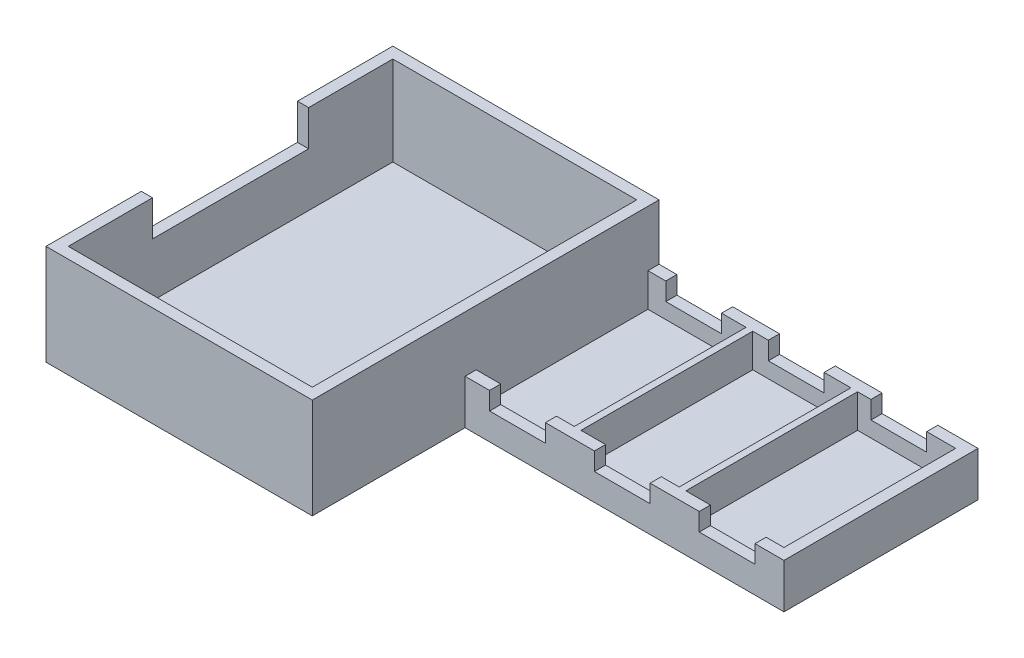
SolidWorks part; units mm, degrees
ref_plane "Frontal Plane" through (0, 0, 0) normal (0, 0, 1) x (1, 0, 0)
ref_plane "Horizontal Plane" through (0, 0, 0) normal (0, 1, 0) x (1, 0, 0)
ref_plane "Profile Plane" through (0, 0, 0) normal (1, 0, 0) x (0, 0, -1)
sketch "Sketch1" plane through (0, 0, 0) normal (0, 1, 0) x (1, 0, 0)
  line L0 (0, 77.75) -> (0, -77.75)
  line L1 (0, 77.75) -> (262.4, 77.75)
  line L2 (0, -77.75) -> (119.4, -77.75)
  line L3 (262.4, 77.75) -> (262.4, -9.25)
  line L4 (262.4, -9.25) -> (119.4, -9.25)
  line L5 (119.4, -9.25) -> (119.4, -77.75)
  line L6 (5, 72.75) -> (257.4, 72.75)
  line L7 (257.4, 72.75) -> (257.4, -4.25)
  line L8 (257.4, -4.25) -> (114.4, -4.25)
  line L9 (114.4, -4.25) -> (114.4, -72.75)
  line L10 (5, -72.75) -> (114.4, -72.75)
  line L11 (5, 72.75) -> (5, -72.75)
  point P4 (0, 0)
  dimension "D1" = 145.5
  dimension "D2" = 109.4
  dimension "D4" = 138
  dimension "D5" = 77
  dimension "D3" = 5
extrude "Boss-Extrude1" add sketch "Sketch1" along normal blind 40
sketch "Sketch3" plane through (0, 0, 0) normal (0, -1, 0) x (1, 0, 0)
  line L0 (119.4, 77.75) -> (119.4, 9.25)
  line L1 (119.4, 77.75) -> (119.4, 9.25)
  line L2 (119.4, 9.25) -> (262.4, 9.25)
  line L3 (119.4, 9.25) -> (262.4, 9.25)
  line L4 (262.4, 9.25) -> (262.4, -77.75)
  line L5 (262.4, 9.25) -> (262.4, -77.75)
  line L6 (262.4, -77.75) -> (0, -77.75)
  line L7 (262.4, -77.75) -> (0, -77.75)
  line L8 (0, -77.75) -> (0, 77.75)
  line L9 (0, -77.75) -> (0, 77.75)
  line L10 (0, 77.75) -> (119.4, 77.75)
  line L11 (0, 77.75) -> (119.4, 77.75)
extrude "Boss-Extrude2" add sketch "Sketch3" along normal blind 5
sketch "Sketch4" plane through (0, 0, 0) normal (0, 1, 0) x (1, 0, 0)
  line L0 (114.4, -4.25) -> (114.4, 72.75)
  line L1 (257.4, 72.75) -> (5, 72.75) construction
  line L2 (114.4, -4.25) -> (119.4, -4.25)
  line L3 (114.4, -4.25) -> (257.4, -4.25) construction
  line L4 (119.4, -4.25) -> (119.4, 72.75)
  line L5 (119.4, 72.75) -> (114.4, 72.75)
  line L7 (163.4, 72.75) -> (163.4, -4.25)
  line L8 (114.4, -4.25) -> (257.4, -4.25) construction
  line L9 (163.4, -4.25) -> (166.4, -4.25)
  line L10 (166.4, -4.25) -> (166.4, 72.75)
  line L11 (257.4, 72.75) -> (5, 72.75) construction
  line L12 (166.4, 72.75) -> (163.4, 72.75)
  line L13 (210.4, 72.75) -> (210.4, -4.25)
  line L14 (210.4, -4.25) -> (213.4, -4.25)
  line L15 (213.4, -4.25) -> (213.4, 72.75)
  line L16 (213.4, 72.75) -> (210.4, 72.75)
  point P20 (145.9914, 71.75)
  dimension "D1" = 3
  dimension "D2" = 44
  dimension "D3" = 44
extrude "Boss-Extrude3" add sketch "Sketch4" along normal up to surface (40 mm away) up to face at (127.2667, 40, 3.0833)
sketch "Sketch5" plane through (0, 40, 0) normal (0, 1, 0) x (1, 0, 0)
  line L0 (119.4, 77.75) -> (119.4, -9.25)
  line L1 (262.4, 77.75) -> (0, 77.75) construction
  line L2 (119.4, -9.25) -> (262.4, -9.25)
  line L3 (262.4, -9.25) -> (262.4, 77.75)
  line L4 (262.4, 77.75) -> (119.4, 77.75)
extrude "Cut-Extrude1" cut sketch "Sketch5" against normal offset from surface (25 mm away) 15 up to face at (141.4, 0, -34.25)
sketch "Sketch6" plane through (0, 15, 0) normal (0, 1, 0) x (1, 0, 0)
  line L0 (130.4, -4.25) -> (130.4, -9.25)
  line L1 (119.4, -4.25) -> (163.4, -4.25) construction
  line L2 (262.4, -9.25) -> (119.4, -9.25) construction
  line L3 (130.4, -9.25) -> (155.4, -9.25)
  line L4 (155.4, -9.25) -> (155.4, -4.25)
  line L5 (119.4, -4.25) -> (163.4, -4.25) construction
  line L6 (155.4, -4.25) -> (130.4, -4.25)
  line L7 (163.4, 72.75) -> (119.4, 72.75) construction
  line L8 (202.4, -4.25) -> (177.4, -4.25)
  line L9 (177.4, -4.25) -> (177.4, -9.25)
  line L10 (177.4, -9.25) -> (202.4, -9.25)
  line L11 (202.4, -9.25) -> (202.4, -4.25)
  line L12 (249.4, -4.25) -> (224.4, -4.25)
  line L13 (224.4, -4.25) -> (224.4, -9.25)
  line L14 (224.4, -9.25) -> (249.4, -9.25)
  line L15 (249.4, -9.25) -> (249.4, -4.25)
  line L16 (155.4, -4.25) -> (202.4, -4.25) construction
  line L17 (127.4, 77.75) -> (127.4, 72.75)
  line L18 (119.4, 77.75) -> (262.4, 77.75) construction
  line L19 (127.4, 72.75) -> (152.4, 72.75)
  line L20 (152.4, 72.75) -> (152.4, 77.75)
  line L21 (152.4, 77.75) -> (127.4, 77.75)
  line L22 (198.4, 77.75) -> (173.4, 77.75)
  line L23 (173.4, 77.75) -> (173.4, 72.75)
  line L24 (173.4, 72.75) -> (198.4, 72.75)
  line L25 (198.4, 72.75) -> (198.4, 77.75)
  line L26 (244.4, 77.75) -> (219.4, 77.75)
  line L27 (219.4, 77.75) -> (219.4, 72.75)
  line L28 (219.4, 72.75) -> (244.4, 72.75)
  line L29 (244.4, 72.75) -> (244.4, 77.75)
  line L30 (152.4, 77.75) -> (198.4, 77.75) construction
  point P12 (141.4, 72.75)
  point P13 (141.4, -4.25)
  point P31 (142.9, -9.25)
  point P32 (139.9, 72.75)
  dimension "D1" = 25
  dimension "D3" = 47
  dimension "D4" = 1.5
  dimension "D5" = 25
  dimension "D7" = 46
  dimension "D8" = 1.5
  dimension "D2" = 3
  dimension "D6" = 3
extrude "Cut-Extrude2" cut sketch "Sketch6" against normal offset from surface (8 mm away) 7 up to face at (141.4, 0, -34.25)
sketch "Sketch7" plane through (0, 40, 0) normal (0, 1, 0) x (1, 0, 0)
  line L0 (0, 35) -> (0, -35)
  line L1 (0, 77.75) -> (0, -77.75) construction
  line L2 (0, -35) -> (5, -35)
  line L3 (5, 72.75) -> (5, -72.75) construction
  line L4 (5, -35) -> (5, 35)
  line L5 (5, 35) -> (0, 35)
  point P5 (0, 0)
  dimension "D1" = 70
extrude "Cut-Extrude3" cut sketch "Sketch7" against normal offset from surface (16 mm away) 24 up to face at (59.7, 0, 0)
sketch "Sketch8" [suppressed] plane through (0, 0, 0) normal (0, 1, 0) x (1, 0, 0)
  line L1 (-0.2725, 127.4404) -> (255.7275, 127.4404)
  line L2 (-0.2725, 127.4404) -> (-0.2725, -128.5596)
  line L3 (-0.2725, -128.5596) -> (255.7275, -128.5596)
  line L4 (255.7275, 127.4404) -> (255.7275, -128.5596)
  line L5 (-0.2725, 127.4404) -> (255.7275, -128.5596) construction
  line L6 (-0.2725, -128.5596) -> (255.7275, 127.4404) construction
  point P0 (127.7275, -0.5596)
  dimension "D1" = 256
  dimension "D2" = 256
